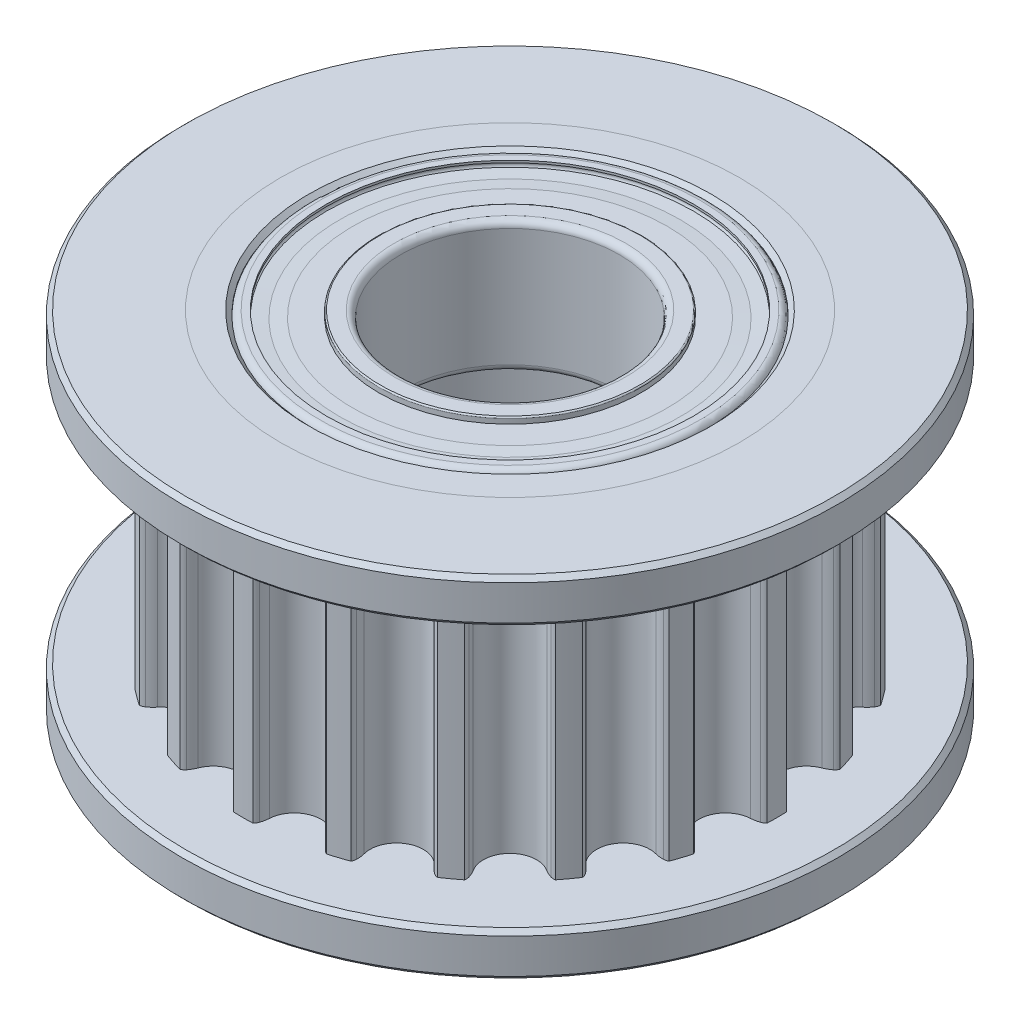
SolidWorks part; units mm, degrees
material "6061-T6 (SS)"
ref_plane "Přední rovina" through (0, 0, 0) normal (0, 0, 1) x (1, 0, 0)
ref_plane "Horní rovina" through (0, 0, 0) normal (0, 1, 0) x (1, 0, 0)
ref_plane "Pravá rovina" through (0, 0, 0) normal (1, 0, 0) x (0, 0, -1)
sketch "Skica1" plane through (0, 0, 0) normal (0, 0, 1) x (1, 0, 0)
  line L0 (4.5, 8) -> (5.25, 8)
  line L1 (5.25, 8) -> (5.25, 7)
  line L2 (5.25, 7) -> (6.11, 7)
  line L3 (6.11, 7) -> (6.11, 1)
  line L4 (6.11, 1) -> (5.25, 1)
  line L5 (5.25, 1) -> (5.25, 0)
  line L6 (5.25, 0) -> (4.5, 0)
  line L8 (4.5, 8) -> (4.5, 5)
  line L9 (4.5, 5) -> (3.5, 5)
  line L10 (3.5, 5) -> (3.5, 3)
  line L11 (3.5, 3) -> (4.5, 3)
  line L12 (4.5, 3) -> (4.5, 0)
  line L13 (0, 0) -> (0, -4.1646) construction
  dimension "D1" = 8
  dimension "D2" = 6
  dimension "D3" = 4.5
  dimension "D4" = 3.5
  dimension "D5" = 6.11
  dimension "D6" = 3
  dimension "D7" = 5.25
revolve "Rotovat1" add sketch "Skica1" angle 360 about L13
chamfer "Zkosení1" distance 0.1 angle 45 4 edges at (0, 3, 3.5) (0, 0, 4.5) (0, 5, 3.5) (0, 8, 4.5)
fillet "Zaoblit1" radius 0.1 2 edges at (0, 3, 4.5) (0, 5, 4.5)
sketch "Skica11" plane through (0, 7, 0) normal (0, 1, 0) x (1, 0, 0)
  line L0 (0, -5.5) -> (0, 5.5) construction
  line L1 (-5.5, 0) -> (5.5, 0) construction
  point P5 (0, 6.1087)
  arc B0 (-3.6824, -4.5256) -> (-4.5256, -3.6824) centre (-4.1938, -4.1938) ccw
  arc B1 (-3.6824, -4.5256) -> (-3.7624, -4.7003) centre (-3.1284, -4.885) ccw
  arc B2 (-3.7624, -4.7003) -> (-3.7672, -4.8088) centre (-3.5429, -4.7643) ccw
  arc B3 (-3.7672, -4.8088) -> (-3.4093, -5.0688) centre (0, 0) ccw
  arc B4 (-3.4093, -5.0688) -> (-3.3076, -5.0308) centre (-3.4362, -4.8418) ccw
  arc B5 (-3.3076, -5.0308) -> (-3.1662, -4.9006) centre (-3.6792, -4.4848) ccw
  arc B6 (-2.1037, -5.442) -> (-3.1662, -4.9006) centre (-2.6926, -5.2845) ccw
  arc B7 (-2.1037, -5.442) -> (-2.1258, -5.6329) centre (-1.4657, -5.6126) ccw
  arc B8 (-2.1258, -5.6329) -> (-2.0968, -5.7376) centre (-1.8973, -5.6259) ccw
  arc B9 (-2.0968, -5.7376) -> (-1.6761, -5.8742) centre (0, 0) ccw
  arc B10 (-1.6761, -5.8742) -> (-1.5911, -5.8066) centre (-1.7719, -5.6667) ccw
  arc B11 (-1.5911, -5.8066) -> (-1.4968, -5.6392) centre (-2.1132, -5.4022) ccw
  arc B12 (-0.319, -5.8257) -> (-1.4968, -5.6392) centre (-0.9278, -5.8579) ccw
  arc B13 (-0.319, -5.8257) -> (-0.2811, -6.0141) centre (0.3404, -5.7909) ccw
  arc B14 (-0.2811, -6.0141) -> (-0.2211, -6.1047) centre (-0.0659, -5.9369) ccw
  arc B15 (-0.2211, -6.1047) -> (0.2211, -6.1047) centre (0, 0) ccw
  arc B16 (0.2211, -6.1047) -> (0.2811, -6.0141) centre (0.0659, -5.9369) ccw
  arc B17 (0.2811, -6.0141) -> (0.319, -5.8257) centre (-0.3404, -5.7909) ccw
  arc B18 (1.4968, -5.6392) -> (0.319, -5.8257) centre (0.9278, -5.8579) ccw
  arc B19 (1.4968, -5.6392) -> (1.5911, -5.8066) centre (2.1132, -5.4022) ccw
  arc B20 (1.5911, -5.8066) -> (1.6761, -5.8742) centre (1.7719, -5.6667) ccw
  arc B21 (1.6761, -5.8742) -> (2.0968, -5.7376) centre (0, 0) ccw
  arc B22 (2.0968, -5.7376) -> (2.1258, -5.6329) centre (1.8973, -5.6259) ccw
  arc B23 (2.1258, -5.6329) -> (2.1037, -5.442) centre (1.4657, -5.6126) ccw
  arc B24 (3.1662, -4.9006) -> (2.1037, -5.442) centre (2.6926, -5.2845) ccw
  arc B25 (3.1662, -4.9006) -> (3.3076, -5.0308) centre (3.6792, -4.4848) ccw
  arc B26 (3.3076, -5.0308) -> (3.4093, -5.0688) centre (3.4362, -4.8418) ccw
  arc B27 (3.4093, -5.0688) -> (3.7672, -4.8088) centre (0, 0) ccw
  arc B28 (3.7672, -4.8088) -> (3.7624, -4.7003) centre (3.5429, -4.7643) ccw
  arc B29 (3.7624, -4.7003) -> (3.6824, -4.5256) centre (3.1284, -4.885) ccw
  arc B30 (4.5256, -3.6824) -> (3.6824, -4.5256) centre (4.1938, -4.1938) ccw
  arc B31 (4.5256, -3.6824) -> (4.7003, -3.7624) centre (4.885, -3.1284) ccw
  arc B32 (4.7003, -3.7624) -> (4.8088, -3.7672) centre (4.7643, -3.5429) ccw
  arc B33 (4.8088, -3.7672) -> (5.0688, -3.4093) centre (0, 0) ccw
  arc B34 (5.0688, -3.4093) -> (5.0308, -3.3076) centre (4.8418, -3.4362) ccw
  arc B35 (5.0308, -3.3076) -> (4.9006, -3.1662) centre (4.4848, -3.6792) ccw
  arc B36 (5.442, -2.1037) -> (4.9006, -3.1662) centre (5.2845, -2.6926) ccw
  arc B37 (5.442, -2.1037) -> (5.6329, -2.1258) centre (5.6126, -1.4657) ccw
  arc B38 (5.6329, -2.1258) -> (5.7376, -2.0968) centre (5.6259, -1.8973) ccw
  arc B39 (5.7376, -2.0968) -> (5.8742, -1.6761) centre (0, 0) ccw
  arc B40 (5.8742, -1.6761) -> (5.8066, -1.5911) centre (5.6667, -1.7719) ccw
  arc B41 (5.8066, -1.5911) -> (5.6392, -1.4968) centre (5.4022, -2.1132) ccw
  arc B42 (5.8257, -0.319) -> (5.6392, -1.4968) centre (5.8579, -0.9278) ccw
  arc B43 (5.8257, -0.319) -> (6.0141, -0.2811) centre (5.7909, 0.3404) ccw
  arc B44 (6.0141, -0.2811) -> (6.1047, -0.2211) centre (5.9369, -0.0659) ccw
  arc B45 (6.1047, -0.2211) -> (6.1047, 0.2211) centre (0, 0) ccw
  arc B46 (6.1047, 0.2211) -> (6.0141, 0.2811) centre (5.9369, 0.0659) ccw
  arc B47 (6.0141, 0.2811) -> (5.8257, 0.319) centre (5.7909, -0.3404) ccw
  arc B48 (5.6392, 1.4968) -> (5.8257, 0.319) centre (5.8579, 0.9278) ccw
  arc B49 (5.6392, 1.4968) -> (5.8066, 1.5911) centre (5.4022, 2.1132) ccw
  arc B50 (5.8066, 1.5911) -> (5.8742, 1.6761) centre (5.6667, 1.7719) ccw
  arc B51 (5.8742, 1.6761) -> (5.7376, 2.0968) centre (0, 0) ccw
  arc B52 (5.7376, 2.0968) -> (5.6329, 2.1258) centre (5.6259, 1.8973) ccw
  arc B53 (5.6329, 2.1258) -> (5.442, 2.1037) centre (5.6126, 1.4657) ccw
  arc B54 (4.9006, 3.1662) -> (5.442, 2.1037) centre (5.2845, 2.6926) ccw
  arc B55 (4.9006, 3.1662) -> (5.0308, 3.3076) centre (4.4848, 3.6792) ccw
  arc B56 (5.0308, 3.3076) -> (5.0688, 3.4093) centre (4.8418, 3.4362) ccw
  arc B57 (5.0688, 3.4093) -> (4.8088, 3.7672) centre (0, 0) ccw
  arc B58 (4.8088, 3.7672) -> (4.7003, 3.7624) centre (4.7643, 3.5429) ccw
  arc B59 (4.7003, 3.7624) -> (4.5256, 3.6824) centre (4.885, 3.1284) ccw
  arc B60 (3.6824, 4.5256) -> (4.5256, 3.6824) centre (4.1938, 4.1938) ccw
  arc B61 (3.6824, 4.5256) -> (3.7624, 4.7003) centre (3.1284, 4.885) ccw
  arc B62 (3.7624, 4.7003) -> (3.7672, 4.8088) centre (3.5429, 4.7643) ccw
  arc B63 (3.7672, 4.8088) -> (3.4093, 5.0688) centre (0, 0) ccw
  arc B64 (3.4093, 5.0688) -> (3.3076, 5.0308) centre (3.4362, 4.8418) ccw
  arc B65 (3.3076, 5.0308) -> (3.1662, 4.9006) centre (3.6792, 4.4848) ccw
  arc B66 (2.1037, 5.442) -> (3.1662, 4.9006) centre (2.6926, 5.2845) ccw
  arc B67 (2.1037, 5.442) -> (2.1258, 5.6329) centre (1.4657, 5.6126) ccw
  arc B68 (2.1258, 5.6329) -> (2.0968, 5.7376) centre (1.8973, 5.6259) ccw
  arc B69 (2.0968, 5.7376) -> (1.6761, 5.8742) centre (0, 0) ccw
  arc B70 (1.6761, 5.8742) -> (1.5911, 5.8066) centre (1.7719, 5.6667) ccw
  arc B71 (1.5911, 5.8066) -> (1.4968, 5.6392) centre (2.1132, 5.4022) ccw
  arc B72 (0.319, 5.8257) -> (1.4968, 5.6392) centre (0.9278, 5.8579) ccw
  arc B73 (0.319, 5.8257) -> (0.2811, 6.0141) centre (-0.3404, 5.7909) ccw
  arc B74 (0.2811, 6.0141) -> (0.2211, 6.1047) centre (0.0659, 5.9369) ccw
  arc B75 (0.2211, 6.1047) -> (-0.2211, 6.1047) centre (0, 0) ccw
  arc B76 (-0.2211, 6.1047) -> (-0.2811, 6.0141) centre (-0.0659, 5.9369) ccw
  arc B77 (-0.2811, 6.0141) -> (-0.319, 5.8257) centre (0.3404, 5.7909) ccw
  arc B78 (-1.4968, 5.6392) -> (-0.319, 5.8257) centre (-0.9278, 5.8579) ccw
  arc B79 (-1.4968, 5.6392) -> (-1.5911, 5.8066) centre (-2.1132, 5.4022) ccw
  arc B80 (-1.5911, 5.8066) -> (-1.6761, 5.8742) centre (-1.7719, 5.6667) ccw
  arc B81 (-1.6761, 5.8742) -> (-2.0968, 5.7376) centre (0, 0) ccw
  arc B82 (-2.0968, 5.7376) -> (-2.1258, 5.6329) centre (-1.8973, 5.6259) ccw
  arc B83 (-2.1258, 5.6329) -> (-2.1037, 5.442) centre (-1.4657, 5.6126) ccw
  arc B84 (-3.1662, 4.9006) -> (-2.1037, 5.442) centre (-2.6926, 5.2845) ccw
  arc B85 (-3.1662, 4.9006) -> (-3.3076, 5.0308) centre (-3.6792, 4.4848) ccw
  arc B86 (-3.3076, 5.0308) -> (-3.4093, 5.0688) centre (-3.4362, 4.8418) ccw
  arc B87 (-3.4093, 5.0688) -> (-3.7672, 4.8088) centre (0, 0) ccw
  arc B88 (-3.7672, 4.8088) -> (-3.7624, 4.7003) centre (-3.5429, 4.7643) ccw
  arc B89 (-3.7624, 4.7003) -> (-3.6824, 4.5256) centre (-3.1284, 4.885) ccw
  arc B90 (-4.5256, 3.6824) -> (-3.6824, 4.5256) centre (-4.1938, 4.1938) ccw
  arc B91 (-4.5256, 3.6824) -> (-4.7003, 3.7624) centre (-4.885, 3.1284) ccw
  arc B92 (-4.7003, 3.7624) -> (-4.8088, 3.7672) centre (-4.7643, 3.5429) ccw
  arc B93 (-4.8088, 3.7672) -> (-5.0688, 3.4093) centre (0, 0) ccw
  arc B94 (-5.0688, 3.4093) -> (-5.0308, 3.3076) centre (-4.8418, 3.4362) ccw
  arc B95 (-5.0308, 3.3076) -> (-4.9006, 3.1662) centre (-4.4848, 3.6792) ccw
  arc B96 (-5.442, 2.1037) -> (-4.9006, 3.1662) centre (-5.2845, 2.6926) ccw
  arc B97 (-5.442, 2.1037) -> (-5.6329, 2.1258) centre (-5.6126, 1.4657) ccw
  arc B98 (-5.6329, 2.1258) -> (-5.7376, 2.0968) centre (-5.6259, 1.8973) ccw
  arc B99 (-5.7376, 2.0968) -> (-5.8742, 1.6761) centre (0, 0) ccw
  arc B100 (-5.8742, 1.6761) -> (-5.8066, 1.5911) centre (-5.6667, 1.7719) ccw
  arc B101 (-5.8066, 1.5911) -> (-5.6392, 1.4968) centre (-5.4022, 2.1132) ccw
  arc B102 (-5.8257, 0.319) -> (-5.6392, 1.4968) centre (-5.8579, 0.9278) ccw
  arc B103 (-5.8257, 0.319) -> (-6.0141, 0.2811) centre (-5.7909, -0.3404) ccw
  arc B104 (-6.0141, 0.2811) -> (-6.1047, 0.2211) centre (-5.9369, 0.0659) ccw
  arc B105 (-6.1047, 0.2211) -> (-6.1047, -0.2211) centre (0, 0) ccw
  arc B106 (-6.1047, -0.2211) -> (-6.0141, -0.2811) centre (-5.9369, -0.0659) ccw
  arc B107 (-6.0141, -0.2811) -> (-5.8257, -0.319) centre (-5.7909, 0.3404) ccw
  arc B108 (-5.6392, -1.4968) -> (-5.8257, -0.319) centre (-5.8579, -0.9278) ccw
  arc B109 (-5.6392, -1.4968) -> (-5.8066, -1.5911) centre (-5.4022, -2.1132) ccw
  arc B110 (-5.8066, -1.5911) -> (-5.8742, -1.6761) centre (-5.6667, -1.7719) ccw
  arc B111 (-5.8742, -1.6761) -> (-5.7376, -2.0968) centre (0, 0) ccw
  arc B112 (-5.7376, -2.0968) -> (-5.6329, -2.1258) centre (-5.6259, -1.8973) ccw
  arc B113 (-5.6329, -2.1258) -> (-5.442, -2.1037) centre (-5.6126, -1.4657) ccw
  arc B114 (-4.9006, -3.1662) -> (-5.442, -2.1037) centre (-5.2845, -2.6926) ccw
  arc B115 (-4.9006, -3.1662) -> (-5.0308, -3.3076) centre (-4.4848, -3.6792) ccw
  arc B116 (-5.0308, -3.3076) -> (-5.0688, -3.4093) centre (-4.8418, -3.4362) ccw
  arc B117 (-5.0688, -3.4093) -> (-4.8088, -3.7672) centre (0, 0) ccw
  arc B118 (-4.8088, -3.7672) -> (-4.7003, -3.7624) centre (-4.7643, -3.5429) ccw
  arc B119 (-4.7003, -3.7624) -> (-4.5256, -3.6824) centre (-4.885, -3.1284) ccw
sketch_block_instance "Blok1-1"
sketch_block "Blok1"
extrude "Odebrat vysunutím1" cut sketch "Skica11" against normal through all flip side to cut
sketch "Skica10" plane through (0, 8, 0) normal (0, 1, 0) x (1, 0, 0)
  circle A0 centre (0, 0) radius 7.5
  circle A1 centre (0, 0) radius 5.25 construction
  circle A2 centre (0, 0) radius 5.25
  dimension "D1" = 15
extrude "Přidat vysunutím1" add sketch "Skica10" against normal up to surface (1 mm away) separate body up to face at (0, 7, 5.25)
sketch "Skica12" plane through (0, 0, 0) normal (0, -1, 0) x (1, 0, 0)
  circle A0 centre (0, 0) radius 7.5
  circle A1 centre (0, 0) radius 5.25 construction
  circle A2 centre (0, 0) radius 5.25
  circle A3 centre (0, 0) radius 7.5 construction
extrude "Přidat vysunutím2" add sketch "Skica12" against normal up to surface (1 mm away) separate body up to face at (0, 1, 5.25)
chamfer "Zkosení2" distance 0.1 angle 45 2 edges at (0, 7, -7.5) (0, 8, 7.5)
chamfer "Zkosení3" distance 0.1 angle 45 2 edges at (0, 0, -7.5) (0, 1, 7.5)
sketch "Skica4" plane through (0, 0, 0) normal (0, 0, 1) x (1, 0, 0)
  line L0 (4.5, 7.85) -> (4.5, 5.15)
  line L1 (4.35, 5) -> (4.2, 5)
  line L2 (4.2, 5) -> (4.2, 5.05)
  line L3 (3.85, 5.2828) -> (4.2132, 5.229)
  line L4 (3.85, 5.2828) -> (3.85, 6.0528)
  line L5 (3.85, 6.9472) -> (3.85, 7.7172)
  line L6 (3.85, 7.7172) -> (4.2132, 7.771)
  line L7 (4.35, 8) -> (4.2, 8)
  line L8 (4.2, 8) -> (4.2, 7.95)
  line L9 (0, 0) -> (0, 18.4294) construction
  line L10 (4.4, 5) -> (-4.4, 5) construction
  arc A0 (4.35, 8) -> (4.5, 7.85) centre (4.35, 7.85) cw
  arc A1 (4.35, 5) -> (4.5, 5.15) centre (4.35, 5.15) ccw
  arc A2 (4.2, 7.95) -> (4.2132, 7.771) centre (4.2, 7.86) cw
  arc A3 (3.85, 6.9472) -> (3.85, 6.0528) centre (3.45, 6.5) cw
  arc A4 (4.2, 5.05) -> (4.2132, 5.229) centre (4.2, 5.14) ccw
  point P26 (4.5, 6.5)
  point P29 (4.275, 5)
  dimension "D3" = 0.09
  dimension "D6" = 0.15
  dimension "D7" = 0.6
  dimension "D1" = 4.5
  dimension "D2" = 3.85
  dimension "D4" = 0.05
  dimension "D5" = 0.15
  dimension "D8" = 0.77
  dimension "D9" = 3
  dimension "D10" = 1.05
revolve "Rotovat2" add sketch "Skica4" angle 360 about L9
sketch "Skica5" plane through (0, 0, 0) normal (0, 0, 1) x (1, 0, 0)
  line L0 (2.5, 7.85) -> (2.5, 5.15)
  line L1 (2.65, 8) -> (2.97, 8)
  line L2 (3, 7.97) -> (3, 7.86)
  line L3 (3, 7.86) -> (3.6, 7.86)
  line L4 (3.6, 7.86) -> (3.9, 7.84)
  line L5 (3.9, 7.84) -> (4.2, 7.86)
  line L6 (4.2, 7.86) -> (4.2, 7.81)
  line L7 (4.2, 7.81) -> (3.9, 7.77)
  line L8 (3.9, 7.77) -> (3.6, 7.77)
  line L9 (3.6, 7.77) -> (3, 7.81)
  line L10 (3, 7.81) -> (3, 6.8969)
  line L11 (2.65, 5) -> (2.97, 5)
  line L12 (0, 0) -> (0, 20.363) construction
  line L13 (3, 5.03) -> (3, 5.14)
  line L21 (3, 5.19) -> (3, 6.1031)
  line L22 (3, 5.14) -> (3.6, 5.14)
  line L23 (3.6, 5.14) -> (3.8962, 5.1917)
  line L24 (3.8962, 5.1917) -> (4.1924, 5.14)
  line L25 (4.1924, 5.14) -> (4.1924, 5.19)
  line L26 (4.1924, 5.19) -> (3.8975, 5.2581)
  line L27 (3.8975, 5.2581) -> (3.5975, 5.2581)
  line L28 (3.5975, 5.2581) -> (3, 5.19)
  line L29 (-4.2, 5) -> (4.2, 5) construction
  arc A0 (2.65, 5) -> (2.5, 5.15) centre (2.65, 5.15) cw
  arc A1 (2.65, 8) -> (2.5, 7.85) centre (2.65, 7.85) ccw
  arc A2 (3, 7.97) -> (2.97, 8) centre (2.97, 7.97) ccw
  arc A3 (3, 5.03) -> (2.97, 5) centre (2.97, 5.03) cw
  arc A4 (3, 6.8969) -> (3, 6.1031) centre (3.45, 6.5) ccw
  dimension "D3" = 0.15
  dimension "D4" = 0.11
  dimension "D5" = 0.03
  dimension "D7" = 0.6
  dimension "D1" = 2.5
  dimension "D2" = 3
  dimension "D6" = 0.6
  dimension "D8" = 0.95
  dimension "D9" = 3
  dimension "D10" = 1.2
  dimension "D11" = 0.3
  dimension "D12" = 0.05
  dimension "D13" = 0.9
  dimension "D14" = 0.6
  dimension "D15" = 0.09
  dimension "D16" = 0.05
  dimension "D17" = 0.05
revolve "Rotovat3" add sketch "Skica5" angle 360 about L12
sketch "Skica6" plane through (0, 0, 0) normal (0, 0, 1) x (1, 0, 0)
  line L0 (3.45, 7.1) -> (3.45, 5.9)
  line L4 (-4.2, 5) -> (4.2, 5) construction
  arc A0 (3.45, 7.1) -> (3.45, 5.9) centre (3.45, 6.5) cw
  dimension "D1" = 0.6
  dimension "D2" = 1.5
  dimension "D3" = 3.45
revolve "Rotovat4" add sketch "Skica6" angle 360 about L0
pattern_circular "Kruhové pole1" count 8 over 360 about axis through (0, 0, 0) along (0, 1, 0) of bodies 105
sketch "Skica7" plane through (0, 0, 0) normal (0, 0, 1) x (1, 0, 0)
  line L0 (4.5, 2.85) -> (4.5, 0.15)
  line L1 (4.35, 0) -> (4.2, 0)
  line L2 (4.2, 0) -> (4.2, 0.05)
  line L3 (3.85, 0.2828) -> (4.2132, 0.229)
  line L4 (3.85, 0.2828) -> (3.85, 1.0528)
  line L5 (3.85, 1.9472) -> (3.85, 2.7172)
  line L6 (3.85, 2.7172) -> (4.2132, 2.771)
  line L7 (4.35, 3) -> (4.2, 3)
  line L8 (4.2, 3) -> (4.2, 2.95)
  line L9 (0, 0) -> (0, 11.2374) construction
  arc A0 (4.35, 3) -> (4.5, 2.85) centre (4.35, 2.85) cw
  arc A1 (4.35, 0) -> (4.5, 0.15) centre (4.35, 0.15) ccw
  arc A2 (4.2, 2.95) -> (4.2132, 2.771) centre (4.2, 2.86) cw
  arc A3 (3.85, 1.9472) -> (3.85, 1.0528) centre (3.45, 1.5) cw
  arc A4 (4.2, 0.05) -> (4.2132, 0.229) centre (4.2, 0.14) ccw
  point P19 (4.5, 1.5)
  point P20 (4.275, 0)
  dimension "D1" = 0.09
  dimension "D4" = 0.15
  dimension "D5" = 0.6
  dimension "D2" = 0.05
  dimension "D3" = 0.15
  dimension "D6" = 0.77
  dimension "D7" = 3
  dimension "D8" = 1.05
  dimension "D9" = 4.5
  dimension "D10" = 3.85
revolve "Rotovat5" add sketch "Skica7" angle 360 about L9
sketch "Skica8" plane through (0, 0, 0) normal (0, 0, 1) x (1, 0, 0)
  line L0 (2.5, 2.85) -> (2.5, 0.15)
  line L1 (2.65, 3) -> (2.97, 3)
  line L2 (3, 2.97) -> (3, 2.86)
  line L3 (3, 2.86) -> (3.6, 2.86)
  line L4 (3.6, 2.86) -> (3.9, 2.84)
  line L5 (3.9, 2.84) -> (4.2, 2.86)
  line L6 (4.2, 2.86) -> (4.2, 2.81)
  line L7 (4.2, 2.81) -> (3.9, 2.77)
  line L8 (3.9, 2.77) -> (3.6, 2.77)
  line L9 (3.6, 2.77) -> (3, 2.81)
  line L10 (3, 2.81) -> (3, 1.8969)
  line L11 (2.65, 0) -> (2.97, 0)
  line L12 (3, 0.03) -> (3, 0.14)
  line L13 (3, 0.19) -> (3, 1.1031)
  line L14 (3, 0.14) -> (3.6, 0.14)
  line L15 (3.6, 0.14) -> (3.8962, 0.1917)
  line L16 (3.8962, 0.1917) -> (4.1924, 0.14)
  line L17 (4.1924, 0.14) -> (4.1924, 0.19)
  line L18 (4.1924, 0.19) -> (3.8975, 0.2581)
  line L19 (3.8975, 0.2581) -> (3.5975, 0.2581)
  line L20 (3.5975, 0.2581) -> (3, 0.19)
  line L21 (0, 0) -> (0, -2.9362) construction
  arc A0 (2.65, 0) -> (2.5, 0.15) centre (2.65, 0.15) cw
  arc A1 (2.65, 3) -> (2.5, 2.85) centre (2.65, 2.85) ccw
  arc A2 (3, 2.97) -> (2.97, 3) centre (2.97, 2.97) ccw
  arc A3 (3, 0.03) -> (2.97, 0) centre (2.97, 0.03) cw
  arc A4 (3, 1.8969) -> (3, 1.1031) centre (3.45, 1.5) ccw
  dimension "D1" = 0.15
  dimension "D2" = 0.03
  dimension "D5" = 0.6
  dimension "D3" = 0.11
  dimension "D4" = 0.6
  dimension "D6" = 0.95
  dimension "D7" = 3
  dimension "D8" = 1.2
  dimension "D9" = 0.3
  dimension "D10" = 0.05
  dimension "D11" = 0.9
  dimension "D12" = 0.6
  dimension "D13" = 0.09
  dimension "D14" = 0.05
  dimension "D15" = 0.05
  dimension "D16" = 2.5
  dimension "D17" = 3
revolve "Rotovat6" add sketch "Skica8" angle 360 about L21
sketch "Skica9" plane through (0, 0, 0) normal (0, 0, 1) x (1, 0, 0)
  line L0 (3.45, 2.1) -> (3.45, 0.9)
  line L1 (0, -2.351) -> (0, 5.6956) construction
  arc A0 (3.45, 2.1) -> (3.45, 0.9) centre (3.45, 1.5) cw
  dimension "D1" = 0.6
  dimension "D2" = 3.45
  dimension "D3" = 1.5
revolve "Rotovat7" add sketch "Skica9" angle 360 about L0
pattern_circular "Kruhové pole3" count 8 over 360 about axis through (0, 0, 0) along (0, 1, 0)
